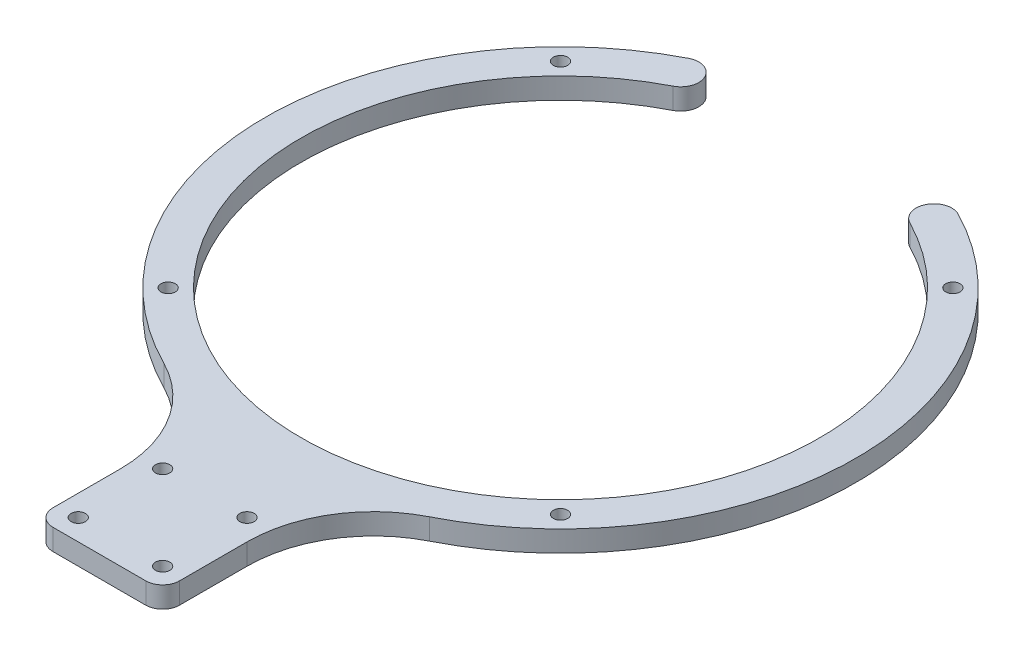
SolidWorks part; units mm, degrees
ref_plane "Plan de face" through (0, 0, 0) normal (0, 0, 1) x (1, 0, 0)
ref_plane "Plan de dessus" through (0, 0, 0) normal (0, 1, 0) x (1, 0, 0)
ref_plane "Plan de droite" through (0, 0, 0) normal (1, 0, 0) x (0, 0, -1)
sketch "Esquisse1" plane through (0, 0, 0) normal (0, 1, 0) x (1, 0, 0)
  line L0 (-30, 58.5182) -> (30, 58.5182) construction
  line L1 (-45, -89.3029) -> (45, -89.3029) construction
  line L2 (-15, -89.3029) -> (-15, -105.3029)
  line L3 (15, -89.3029) -> (15, -105.3029)
  line L4 (11, -109.3029) -> (-11, -109.3029)
  arc A0 (28.0657, 54.7451) -> (-28.0657, 54.7451) centre (0, 0) cw
  arc A1 (30, 58.5182) -> (-30, 58.5182) centre (0, 0) cw construction
  arc A2 (-31.9343, 62.2913) -> (-31.5, -62.512) centre (0, 0) ccw
  arc A3 (-31.9343, 62.2913) -> (-28.0657, 54.7451) centre (-30, 58.5182) cw
  arc A4 (28.0657, 54.7451) -> (31.9343, 62.2913) centre (30, 58.5182) cw
  arc A5 (31.9343, 62.2913) -> (31.5, -62.512) centre (0, 0) cw
  arc A6 (-31.5, -62.512) -> (-15, -89.3029) centre (-45, -89.3029) cw
  arc A7 (31.5, -62.512) -> (15, -89.3029) centre (45, -89.3029) ccw
  arc A8 (-15, -105.3029) -> (-11, -109.3029) centre (-11, -105.3029) ccw
  arc A9 (15, -105.3029) -> (11, -109.3029) centre (11, -105.3029) cw
  point P12 (0, 58.5182)
  point P13 (0, -89.3029)
  dimension "D1" = 65.76
  dimension "D2" = 70
  dimension "D6" = 4
  dimension "D7" = 30
  dimension "D3" = 60
  dimension "D4" = 30
  dimension "D5" = 20
extrude "Boss.-Extru.1" add sketch "Esquisse1" along normal blind 5
hole_wizard "Dégagement M31" positions "Esquisse2" profile "Esquisse3" hole size "M3" standard "DIN" end condition through all
sketch "Esquisse2" plane through (0, 5, 0) normal (0, 1, 0) x (1, 0, 0)
  line L1 (46.5, -46.5) -> (-46.5, -46.5) construction
  line L2 (46.5, -46.5) -> (46.5, 46.5) construction
  line L3 (46.5, 46.5) -> (-46.5, 46.5) construction
  line L4 (-46.5, -46.5) -> (-46.5, 46.5) construction
  line L5 (46.5, -46.5) -> (-46.5, 46.5) construction
  line L6 (46.5, 46.5) -> (-46.5, -46.5) construction
  line L8 (10, -104.3029) -> (-10, -104.3029) construction
  line L9 (10, -104.3029) -> (10, -84.3029) construction
  line L10 (10, -84.3029) -> (-10, -84.3029) construction
  line L11 (-10, -104.3029) -> (-10, -84.3029) construction
  line L12 (10, -104.3029) -> (-10, -84.3029) construction
  line L13 (10, -84.3029) -> (-10, -104.3029) construction
  line L14 (-11, -109.3029) -> (11, -109.3029) construction
  point P0 (46.5, 46.5)
  point P2 (46.5, -46.5)
  point P4 (-46.5, -46.5)
  point P6 (-46.5, 46.5)
  point P8 (-10, -84.3029)
  point P10 (10, -84.3029)
  point P12 (10, -104.3029)
  point P14 (-10, -104.3029)
  point P305 (0, -94.3029)
  dimension "D1" = 93
  dimension "D2" = 20
  dimension "D3" = 20
  dimension "D4" = 5
sketch "Esquisse3" plane through (46.5, 5, -46.5) normal (1, 0, 0) x (0, 0, 1)
  line L0 (0, 0) -> (0, 5)
  line L1 (0, 5) -> (1.7, 5)
  line L2 (1.7, 5) -> (1.7, 0)
  line L5 (1.7, 0) -> (0, 0)
  line L11 (0, -6.35) -> (0, 107.95) construction
  dimension "Diamètre du perçage jusqu'au prochain" = 3.4
  dimension "Profondeur du perçage jusqu'au prochain" = 5
equation "\"d\"= 20mm"
equation "\"D3@Esquisse2\"=\"d\""
equation "\"D2@Esquisse2\"=\"d\""
